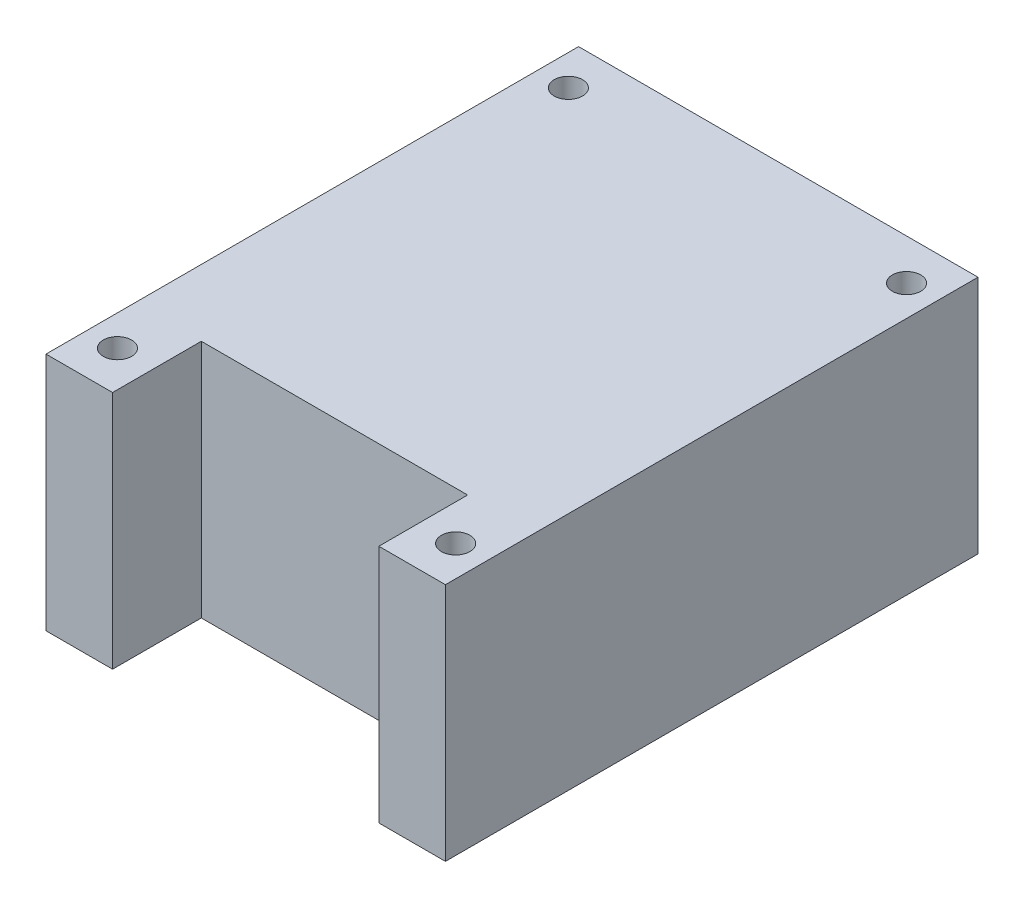
SolidWorks part; units mm, degrees
ref_plane "Plan de face" through (0, 0, 0) normal (0, 0, 1) x (1, 0, 0)
ref_plane "Plan de dessus" through (0, 0, 0) normal (0, 1, 0) x (1, 0, 0)
ref_plane "Plan de droite" through (0, 0, 0) normal (1, 0, 0) x (0, 0, -1)
sketch "Esquisse1" plane through (0, 0, 0) normal (0, 1, 0) x (1, 0, 0)
  line L1 (-22.5, -30) -> (22.5, -30)
  line L2 (-22.5, -30) -> (-22.5, 30)
  line L3 (-22.5, 30) -> (22.5, 30)
  line L4 (22.5, -30) -> (22.5, 30)
  line L5 (-22.5, -30) -> (22.5, 30) construction
  line L6 (-22.5, 30) -> (22.5, -30) construction
  point P0 (0, 0)
  dimension "D1" = 60
  dimension "D2" = 45
extrude "Boss.-Extru.1" add sketch "Esquisse1" along normal blind 27
hole_wizard "Dégagement M31" positions "Esquisse2" profile "Esquisse3" hole size "M3" standard "Ansi Metric" end condition through all
sketch "Esquisse2" plane through (0, 27, 0) normal (0, 1, 0) x (1, 0, 0)
  line L0 (-19.05, 25.4) -> (19.05, -25.4) construction
  line L2 (19.05, 25.4) -> (-19.05, -25.4) construction
  line L4 (22.5, 30) -> (-22.5, 30) construction
  line L5 (22.5, -30) -> (22.5, 30) construction
  point P0 (-19.05, 25.4)
  point P2 (19.05, 25.4)
  point P4 (19.05, -25.4)
  point P6 (-19.05, -25.4)
  point P24 (0, 30)
  point P25 (0, 0)
  point P28 (22.5, 0)
  dimension "D1" = 50.8
  dimension "D2" = 38.1
sketch "Esquisse3" plane through (-19.05, 27, -25.4) normal (1, 0, 0) x (0, 0, 1)
  line L0 (0, 0) -> (0, 27)
  line L1 (0, 27) -> (1.6, 27)
  line L2 (1.6, 27) -> (1.6, 0)
  line L5 (1.6, 0) -> (0, 0)
  line L11 (0, -6.35) -> (0, 107.95) construction
  dimension "Diamètre du perçage jusqu'au prochain" = 3.2
  dimension "Profondeur du perçage jusqu'au prochain" = 27
sketch "Esquisse4" plane through (0, 0, 0) normal (0, -1, 0) x (1, 0, 0)
  line L0 (-22.5, 30) -> (22.5, 30) construction
  line L1 (-15, 20) -> (15, 20)
  line L2 (-15, 20) -> (-15, 30)
  line L3 (-15, 30) -> (15, 30)
  line L4 (15, 20) -> (15, 30)
  line L5 (-15, 20) -> (15, 30) construction
  line L6 (-15, 30) -> (15, 20) construction
  line L7 (-22.5, -30) -> (-22.5, 30) construction
  point P0 (0, 25)
  dimension "D1" = 0
  dimension "D2" = 7.5
  dimension "D3" = 30
  dimension "D4" = 10
extrude "Enlèv. mat.-Extru.1" cut sketch "Esquisse4" against normal up to surface (27 mm away) up to face at (-19.05, 27, -23.8)
